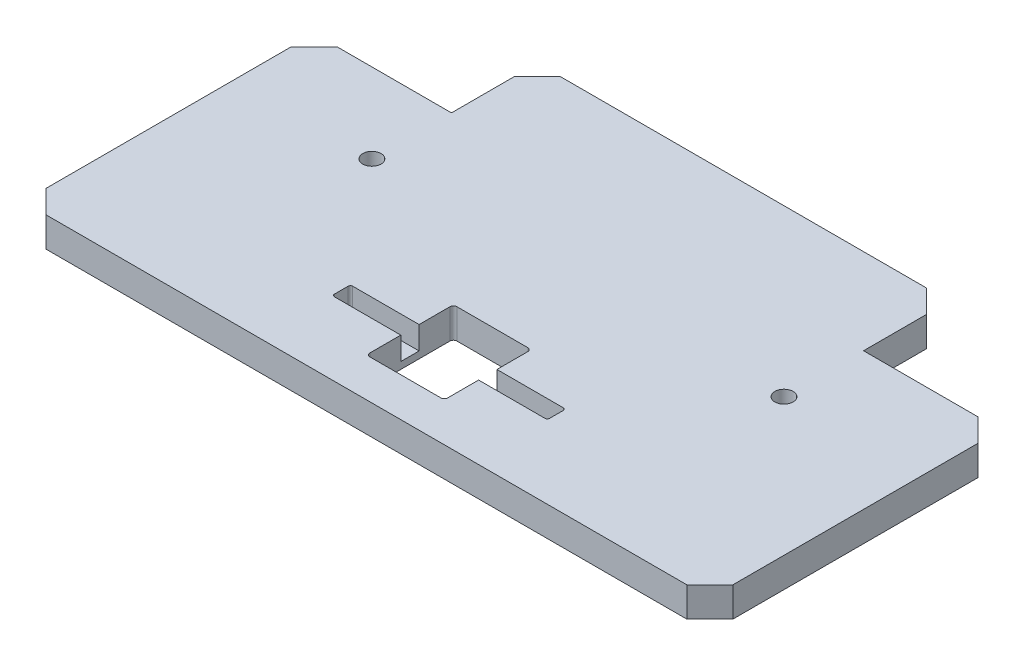
SolidWorks part; units mm, degrees
ref_plane "Front Plane" through (0, 0, 0) normal (0, 0, 1) x (1, 0, 0)
ref_plane "Top Plane" through (0, 0, 0) normal (0, 1, 0) x (1, 0, 0)
ref_plane "Right Plane" through (0, 0, 0) normal (1, 0, 0) x (0, 0, -1)
sketch "Sketch1" plane through (0, 0, 0) normal (0, 1, 0) x (1, 0, 0)
  line L1 (-75, 31.6575) -> (75, 31.6575)
  line L2 (-75, 31.6575) -> (-75, -31.6575)
  line L3 (-75, -31.6575) -> (75, -31.6575)
  line L4 (75, 31.6575) -> (75, -31.6575)
  line L5 (-75, 31.6575) -> (75, -31.6575) construction
  line L6 (-75, -31.6575) -> (75, 31.6575) construction
  point P0 (0, 0)
  dimension "D1" = 63.315
  dimension "D2" = 150
extrude "Boss-Extrude1" add sketch "Sketch1" along normal blind 6.5
sketch "Sketch3" plane through (0, 0, -31.6575) normal (0, 0, -1) x (-1, 0, 0)
  line L0 (-75, 0) -> (75, 0) construction
  line L1 (-75, 6.5) -> (-45, 6.5)
  line L2 (-75, 6.5) -> (-75, 0)
  line L3 (-75, 0) -> (-45, 0)
  line L4 (-45, 6.5) -> (-45, 0)
  line L6 (75, 6.5) -> (45, 6.5)
  line L7 (75, 6.5) -> (75, 0)
  line L8 (75, 0) -> (45, 0)
  line L9 (45, 6.5) -> (45, 0)
  dimension "D1" = 30
  dimension "D2" = 30
extrude "Cut-Extrude1" cut sketch "Sketch3" against normal blind 18.75
chamfer "Chamfer1" distance 5 angle 45 4 edges at (75, 3.25, -12.9075) (45, 3.25, -31.6575) (-45, 3.25, -31.6575) (-75, 3.25, -12.9075)
sketch "Sketch5" plane through (0, 0, 0) normal (0, -1, 0) x (1, 0, 0)
  line L0 (75, 4.4725) -> (-75, 4.4725) construction
  line L1 (75, 31.6575) -> (75, -7.9075) construction
  line L2 (-75, -7.9075) -> (-75, 31.6575) construction
  line L3 (40, -31.6575) -> (-40, -31.6575) construction
  circle A0 centre (45, 4.4725) radius 5
  circle A1 centre (-45, 4.4725) radius 5
  dimension "D2" = 30
  dimension "D1" = 36.13
  dimension "D3" = 30
extrude "Boss-Extrude3" add sketch "Sketch5" along normal blind 17.5
fillet "Fillet1" radius 5 2 edges at (-45, 0, 9.4725) (45, 0, 9.4725)
sketch "Sketch6" plane through (0, -17.5, 0) normal (0, -1, 0) x (1, 0, 0)
  circle A0 centre (45, 4.4725) radius 3.5
extrude "Cut-Extrude2" cut sketch "Sketch6" against normal blind 17.5
sketch "Sketch7" plane through (0, -17.5, 0) normal (0, -1, 0) x (1, 0, 0)
  circle A0 centre (-45, 4.4725) radius 3.5
extrude "Cut-Extrude3" cut sketch "Sketch7" against normal blind 17.5
sketch "Sketch8" plane through (0, 0, 0) normal (0, -1, 0) x (1, 0, 0)
  circle A0 centre (45, 4.4725) radius 2
  circle A1 centre (-45, 4.4725) radius 2
extrude "Cut-Extrude4" cut sketch "Sketch8" against normal blind 6.5
sketch "Sketch11" plane through (0, 0, 31.6575) normal (0, 0, 1) x (1, 0, 0)
  line L1 (-75, 6.5) -> (75, 6.5)
  line L2 (-75, 6.5) -> (-75, 0)
  line L3 (-75, 0) -> (75, 0)
  line L4 (75, 6.5) -> (75, 0)
extrude "Boss-Extrude4" add sketch "Sketch11" along normal blind 19
sketch "Sketch12" plane through (0, 6.5, 0) normal (0, 1, 0) x (1, 0, 0)
  line L0 (-64.6496, -50.6575) -> (-64.6496, -31.6575) construction
  line L1 (75, -50.6575) -> (-75, -50.6575) construction
  line L2 (-64.6496, -41.1575) -> (11.8524, -41.1575) construction
  line L3 (0, 31.6575) -> (0, -50.6575) construction
  line L4 (40, 31.6575) -> (-40, 31.6575) construction
  line L5 (-8.5, -32.6675) -> (-75, -32.6675) construction
  line L6 (0, -32.6675) -> (-8.5, -32.6675) construction
  line L7 (0, -32.6675) -> (8.5, -32.6675) construction
  line L8 (-8.5, -32.6675) -> (-8.5, -42.1675) construction
  line L9 (8.5, -32.6675) -> (8.5, -42.1675) construction
  line L10 (-8.5, -32.6675) -> (-8.5, -23.1675) construction
  line L11 (-75, 7.9075) -> (-75, -50.6575) construction
  line L12 (-8.5, -23.1675) -> (8.5, -23.1675)
  line L13 (-8.5, -23.1675) -> (-8.5, -42.1675)
  line L14 (-8.5, -42.1675) -> (8.5, -42.1675)
  line L15 (8.5, -23.1675) -> (8.5, -42.1675)
  line L16 (8.5, -32.6675) -> (75, -32.6675) construction
  line L17 (75, -50.6575) -> (75, 7.9075) construction
  line L18 (-8.5, -31.1675) -> (-23.5, -31.1675) construction
  line L19 (-8.5, -34.1675) -> (-23.5, -34.1675) construction
  line L20 (8.5, -31.1675) -> (23.5, -31.1675) construction
  line L25 (8.5, -34.1675) -> (23.5, -34.1675) construction
  dimension "D1" = 19
  dimension "D2" = 15
  dimension "D3" = 8.5
  dimension "D4" = 8.5
  dimension "D5" = 9.5
  dimension "D6" = 9.5
  dimension "D7" = 1.5
  dimension "D8" = 1.5
  dimension "D9" = 15
extrude "Cut-Extrude5" cut sketch "Sketch12" against normal blind 19
sketch "Sketch13" plane through (0, 6.5, 0) normal (0, 1, 0) x (1, 0, 0)
  line L0 (-8.5, -32.6675) -> (-75, -32.6675) construction
  line L1 (-8.5, -23.1675) -> (-8.5, -42.1675) construction
  line L2 (-75, 7.9075) -> (-75, -50.6575) construction
  line L3 (8.5, -32.6675) -> (75, -32.6675) construction
  line L4 (8.5, -42.1675) -> (8.5, -23.1675) construction
  line L5 (75, -50.6575) -> (75, 7.9075) construction
  line L6 (-8.5, -30.6675) -> (-23.5, -30.6675) construction
  line L7 (-8.5, -34.6675) -> (-23.5, -34.6675) construction
  line L8 (8.5, -30.6675) -> (23.5, -30.6675) construction
  line L9 (-23.5, -30.6675) -> (-8.5, -30.6675)
  line L10 (-23.5, -30.6675) -> (-23.5, -34.6675)
  line L11 (-23.5, -34.6675) -> (-8.5, -34.6675)
  line L12 (-8.5, -30.6675) -> (-8.5, -34.6675)
  line L13 (8.5, -34.6675) -> (23.5, -34.6675) construction
  line L15 (23.5, -30.6675) -> (8.5, -30.6675)
  line L16 (23.5, -30.6675) -> (23.5, -34.6675)
  line L17 (23.5, -34.6675) -> (8.5, -34.6675)
  line L18 (8.5, -30.6675) -> (8.5, -34.6675)
  dimension "D1" = 15
  dimension "D2" = 2
  dimension "D3" = 2
  dimension "D4" = 15
extrude "Cut-Extrude6" cut sketch "Sketch13" against normal blind 5
fillet "Fillet2" radius 0.5 4 edges at (23.5, 4, 34.6675) (-23.5, 4, 34.6675) (23.5, 4, 30.6675) (-23.5, 4, 30.6675)
fillet "Fillet3" radius 0.75 4 edges at (-8.5, 3.25, 42.1675) (8.5, 3.25, 42.1675) (8.5, 3.25, 23.1675) (-8.5, 3.25, 23.1675)
chamfer "Chamfer2" distance 5 angle 45 2 edges at (75, 3.25, 50.6575) (-75, 3.25, 50.6575)
